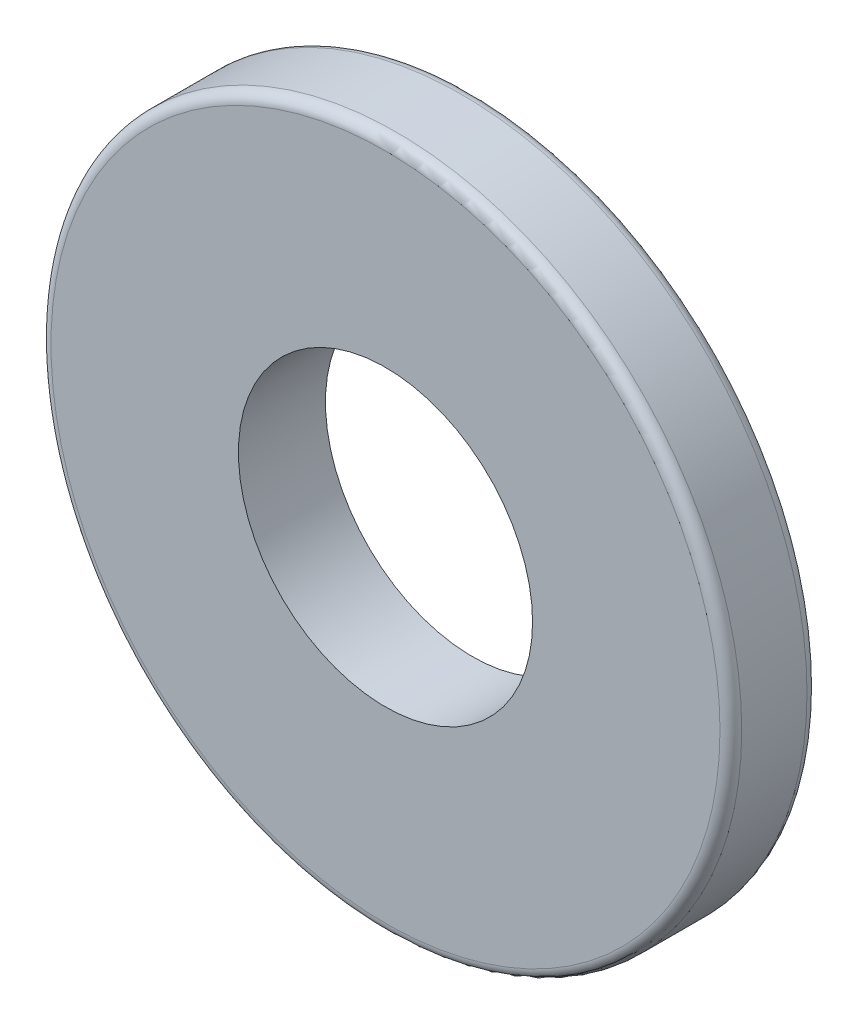
SolidWorks part; units mm, degrees
ref_plane "Front Plane" through (0, 0, 0) normal (0, 0, 1) x (1, 0, 0)
ref_plane "Top Plane" through (0, 0, 0) normal (0, 1, 0) x (1, 0, 0)
ref_plane "Right Plane" through (0, 0, 0) normal (1, 0, 0) x (0, 0, -1)
sketch "Sketch1" plane through (0, 0, 0) normal (0, 0, 1) x (1, 0, 0)
  circle A0 centre (0, 0) radius 3.38
  circle A2 centre (0, 0) radius 7.9375
  dimension "D1" = 15.875
  dimension "D2" = 6.76
extrude "Boss-Extrude1" add sketch "Sketch1" along normal blind 2
fillet "Fillet1" radius 0.25 2 edges at (7.9375, 0, 0) (7.9375, 0, 2)
